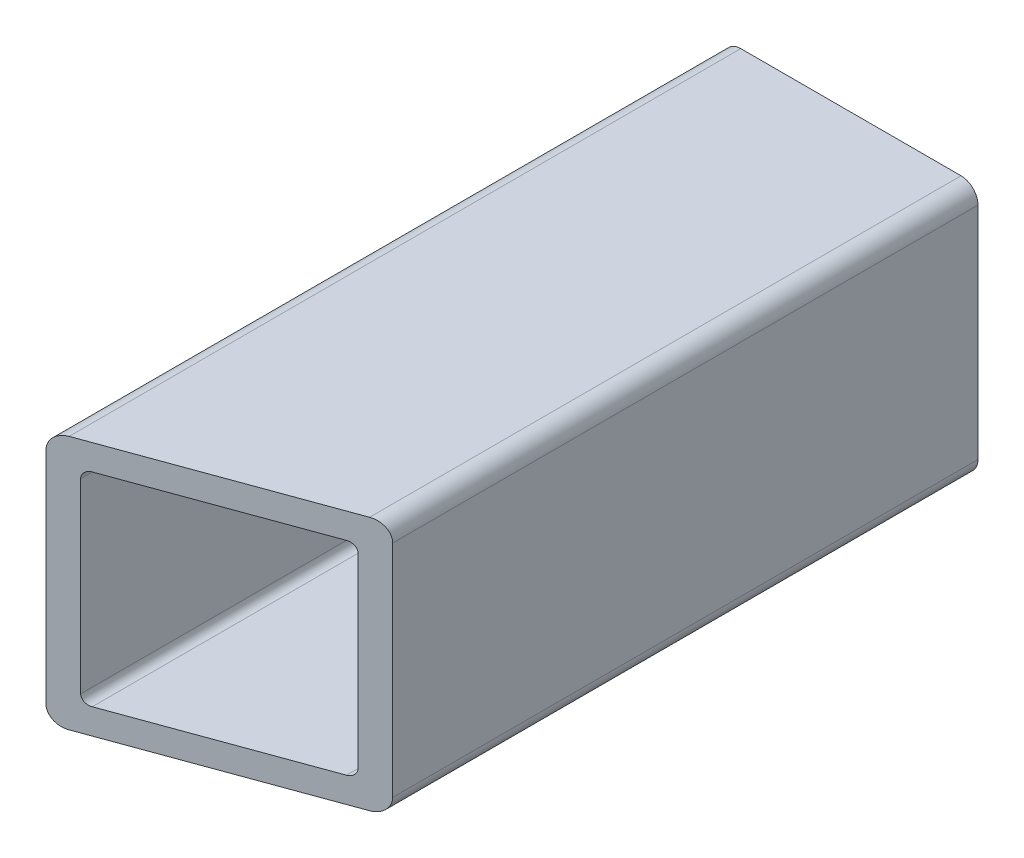
SolidWorks part; units mm, degrees
material "1.0553 (S355J0)"
ref_plane "Płaszczyzna przednia" through (0, 0, 0) normal (0, 0, 1) x (1, 0, 0)
ref_plane "Płaszczyzna górna" through (0, 0, 0) normal (0, 1, 0) x (1, 0, 0)
ref_plane "Płaszczyzna prawa" through (0, 0, 0) normal (1, 0, 0) x (0, 0, -1)
sketch "Szkic1" plane through (0, 0, 0) normal (0, 0, 1) x (1, 0, 0)
  line L0 (-13, -3) -> (13, -3)
  line L1 (-15, -1) -> (-15, 25)
  line L2 (-13, 27) -> (13, 27)
  line L3 (15, -1) -> (15, 25)
  line L4 (-11, 0) -> (11, 0)
  line L5 (-12, 1) -> (-12, 23)
  line L6 (-11, 24) -> (11, 24)
  line L7 (12, 1) -> (12, 23)
  arc A0 (-15, -1) -> (-13, -3) centre (-13, -1) ccw
  arc A1 (13, -3) -> (15, -1) centre (13, -1) ccw
  arc A2 (15, 25) -> (13, 27) centre (13, 25) ccw
  arc A3 (-13, 27) -> (-15, 25) centre (-13, 25) ccw
  arc A4 (-12, 1) -> (-11, 0) centre (-11, 1) ccw
  arc A5 (11, 0) -> (12, 1) centre (11, 1) ccw
  arc A6 (12, 23) -> (11, 24) centre (11, 23) ccw
  arc A7 (-11, 24) -> (-12, 23) centre (-11, 23) ccw
  point P24 (0, 0)
  dimension "D1" = 2
  dimension "D6" = 1
  dimension "D2" = 3
  dimension "D3" = 3
  dimension "D4" = 3
  dimension "D5" = 3
  dimension "D7" = 30
  dimension "D8" = 30
extrude "Dodanie-wyciągnięcie1" add sketch "Szkic1" along normal blind 80
sketch "Szkic2" plane through (0, -3, 0) normal (0, -1, 0) x (1, 0, 0)
  line L0 (-15, 80) -> (63.5223, 51.4202)
  line L1 (-13, 80) -> (13, 80) construction
  line L2 (-15, 80) -> (63.5223, 80)
  line L3 (63.5223, 80) -> (63.5223, 51.4202)
  dimension "D1" = 20
extrude "Wytnij-wyciągnięcie1" cut sketch "Szkic2" against normal blind 70
